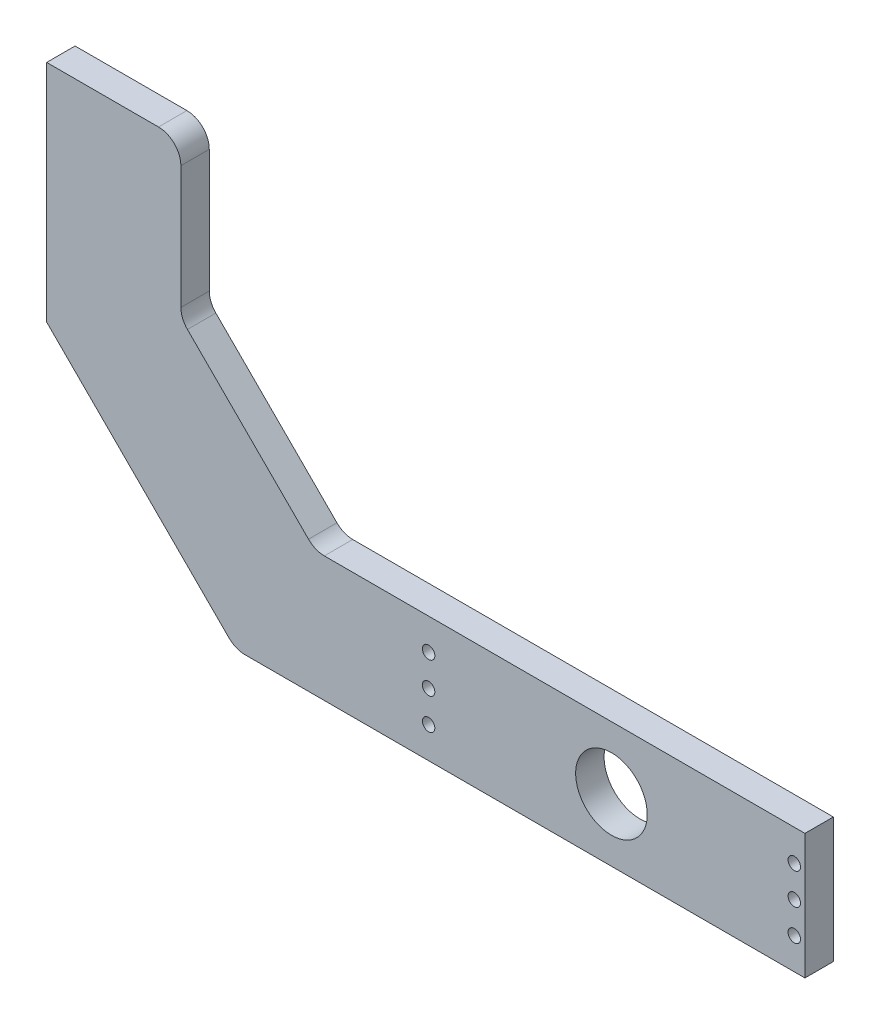
SolidWorks part; units mm, degrees
material "3.0205 (EN AW-1200)"
ref_plane "Plano frontal" through (0, 0, 0) normal (0, 0, 1) x (1, 0, 0)
ref_plane "Plano superior" through (0, 0, 0) normal (0, 1, 0) x (1, 0, 0)
ref_plane "Plano direito" through (0, 0, 0) normal (1, 0, 0) x (0, 0, -1)
sketch "Esboço1" plane through (0, 0, 0) normal (0, 0, 1) x (1, 0, 0)
  line L0 (-114.286, -92.024) -> (224.714, -92.024)
  line L1 (-54.286, 92.976) -> (-114.286, 92.976)
  line L2 (-114.286, 92.976) -> (-114.286, -92.024)
  line L3 (-54.286, 23.976) -> (-54.286, -36.024) construction
  line L4 (-54.286, -36.024) -> (5.714, -36.024) construction
  line L5 (-54.286, 92.976) -> (-54.286, 23.976)
  line L6 (224.714, -92.024) -> (224.714, -36.024)
  line L7 (224.714, -36.024) -> (5.714, -36.024)
  line L8 (5.714, -36.024) -> (-54.286, 23.976)
  dimension "D1" = 219
  dimension "D2" = 56
  dimension "D3" = 339
  dimension "D4" = 185
extrude "Ressalto-extrusão1" add sketch "Esboço1" along normal blind 12.7
sketch "Esboço3" plane through (0, 0, 12.7) normal (0, 0, 1) x (1, 0, 0)
  line L0 (-114.286, -92.024) -> (224.714, -92.024) construction
  circle A1 centre (138.214, -64.024) radius 16
  dimension "D1" = 32
  dimension "D2" = 86.5
  dimension "D3" = 28
extrude "Circulo rolamento" cut sketch "Esboço3" against normal up to next
sketch "Esboço6" plane through (-114.286, 0, 0) normal (-1, 0, 0) x (0, 0, 1)
  line L0 (7.9, 92.976) -> (7.9, -7.024) construction
  line L2 (12.7, 92.976) -> (12.7, -92.024) construction
  circle A0 centre (7.9, 67.976) radius 2.5
  circle A1 centre (7.9, 42.976) radius 2.5
  circle A2 centre (7.9, 17.976) radius 2.5
  dimension "D1" = 5
  dimension "D2" = 5
  dimension "D3" = 5
  dimension "D4" = 25
  dimension "D5" = 25
  dimension "D6" = 4.8
extrude "Corte-extrusão4" cut sketch "Esboço6" against normal blind 30
sketch "Esboço9" plane through (0, 0, 12.7) normal (0, 0, 1) x (1, 0, 0)
  line L0 (-29.8419, -92.024) -> (-114.286, -7.5799)
  line L1 (-114.286, -92.024) -> (224.714, -92.024) construction
  line L2 (-114.286, 92.976) -> (-114.286, -92.024) construction
  line L3 (-114.286, -7.5799) -> (-114.286, -92.024)
  line L4 (-114.286, -92.024) -> (-29.8419, -92.024)
  dimension "D1" = 45
extrude "Corte-extrusão6" cut sketch "Esboço9" against normal up to next
sketch "Esboço10" plane through (0, 0, 12.7) normal (0, 0, 1) x (1, 0, 0)
  line L2 (56.474, -50.024) -> (56.474, -78.024) construction
  line L3 (224.714, -92.024) -> (224.714, -36.024) construction
  line L4 (224.714, -36.024) -> (5.714, -36.024) construction
  circle A0 centre (56.474, -50.024) radius 2.78
  circle A1 centre (56.474, -64.024) radius 2.78
  circle A2 centre (56.474, -78.024) radius 2.78
  dimension "D1" = 5.56
  dimension "D2" = 5.56
  dimension "D3" = 5.56
  dimension "D4" = 14
  dimension "D6" = 168.24
  dimension "D7" = 14
extrude "Corte-extrusão7" cut sketch "Esboço10" against normal up to next
sketch "Esboço12" plane through (0, 0, 12.7) normal (0, 0, 1) x (1, 0, 0)
  line L0 (219.954, -50.024) -> (219.954, -78.024) construction
  line L1 (224.714, -36.024) -> (5.714, -36.024) construction
  line L3 (224.714, -92.024) -> (224.714, -36.024) construction
  line L4 (-29.8419, -92.024) -> (224.714, -92.024) construction
  circle A0 centre (219.954, -78.024) radius 2.78
  circle A1 centre (219.954, -64.024) radius 2.78
  circle A2 centre (219.954, -50.024) radius 2.78
  dimension "D1" = 5.56
  dimension "D2" = 5.56
  dimension "D3" = 5.56
  dimension "D4" = 4.76
  dimension "D5" = 14
  dimension "D7" = 14
extrude "Corte-extrusão8" cut sketch "Esboço12" against normal up to next
fillet "Filete1" radius 10 4 edges at (-54.286, 23.976, 6.35) (5.714, -36.024, 6.35) (-29.8419, -92.024, 6.35) (-54.286, 92.976, 6.35)
